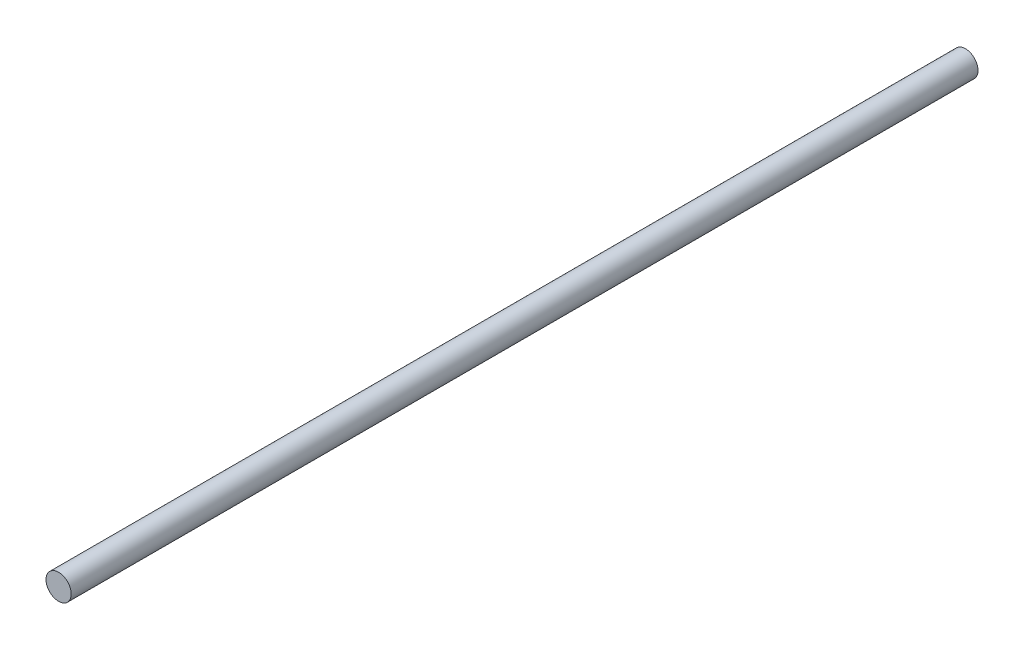
SolidWorks part; units mm, degrees
ref_plane "Front Plane" through (0, 0, 0) normal (0, 0, 1) x (1, 0, 0)
ref_plane "Top Plane" through (0, 0, 0) normal (0, 1, 0) x (1, 0, 0)
ref_plane "Right Plane" through (0, 0, 0) normal (1, 0, 0) x (0, 0, -1)
sketch "Sketch1" plane through (0, 0, 0) normal (0, 0, 1) x (1, 0, 0)
  circle A0 centre (0, 0) radius 5
  dimension "D1" = 10
extrude "Boss-Extrude1" add sketch "Sketch1" along normal blind 360
